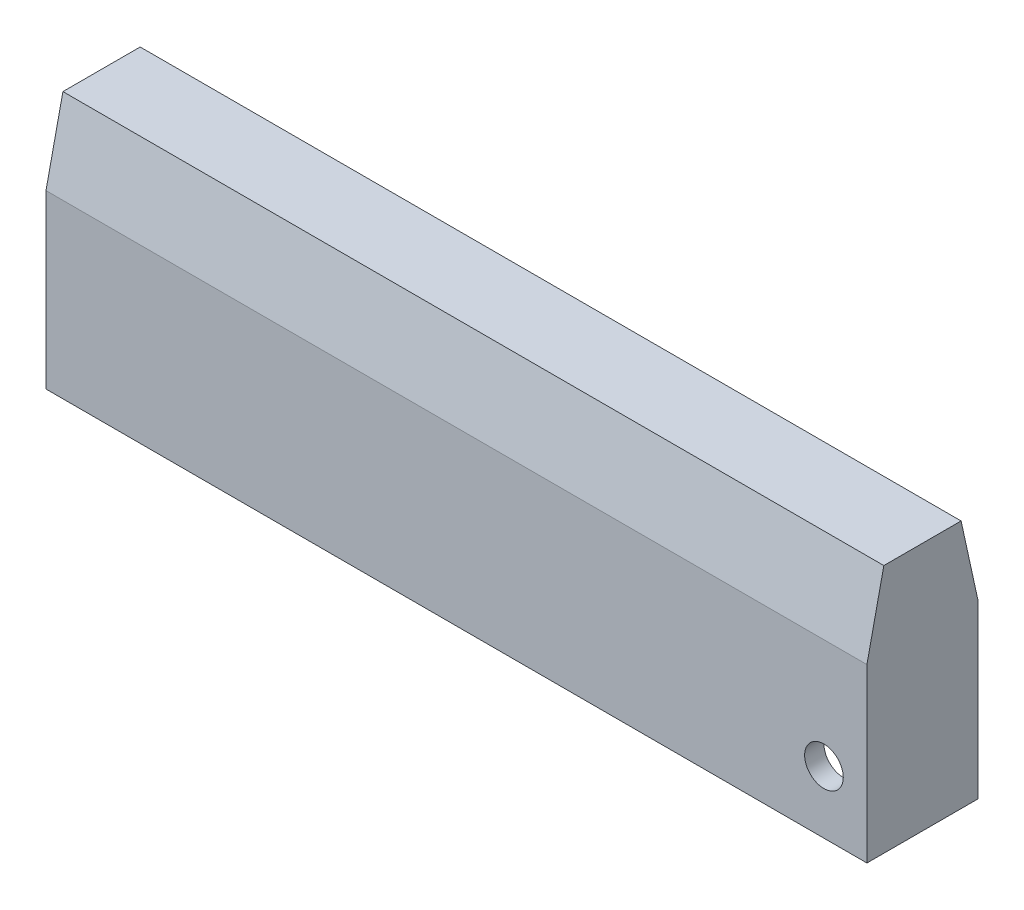
SolidWorks part; units mm, degrees
ref_plane "Front Plane" through (0, 0, 0) normal (0, 0, 1) x (1, 0, 0)
ref_plane "Top Plane" through (0, 0, 0) normal (0, 1, 0) x (1, 0, 0)
ref_plane "Right Plane" through (0, 0, 0) normal (1, 0, 0) x (0, 0, -1)
sketch "Sketch1" plane through (0, 0, 0) normal (0, 1, 0) x (1, 0, 0)
  line L1 (-69, -5.75) -> (69, -5.75)
  line L2 (-69, -5.75) -> (-69, 5.75)
  line L3 (-69, 5.75) -> (69, 5.75)
  line L4 (69, -5.75) -> (69, 5.75)
  line L5 (-69, -5.75) -> (69, 5.75) construction
  line L6 (-69, 5.75) -> (69, -5.75) construction
  point P0 (0, 0)
  dimension "D1" = 11.5
  dimension "D2" = 138
extrude "Boss-Extrude1" add sketch "Sketch1" against normal blind 17.8 and the other way blind 8 contours L2 L3 L4 L1
sketch "Sketch8" plane through (0, 0, 5.75) normal (0, 0, 1) x (1, 0, 0)
  line L0 (69, 8) -> (51.2, -17.8) construction
  line L1 (-69, -17.8) -> (69, -17.8) construction
  line L3 (60.1, -4.9) -> (69, -4.9) construction
  line L4 (69, -17.8) -> (69, 8) construction
  line L5 (64.55, -4.9) -> (64.55, -17.8) construction
  circle A0 centre (64.55, -11.35) radius 2
  dimension "D1" = 4
extrude "Cut-Extrude4" cut sketch "Sketch8" against normal up to surface (11.5 mm away) up to face at (0, -4.9, -5.75)
chamfer "Chamfer2" distance 8 distance2 1.75 1 edges at (0, 8, 5.75)
chamfer "Chamfer3" distance 1.75 distance2 8 1 edges at (0, 8, -5.75)
sketch "Sketch11" plane through (0, -17.8, 0) normal (0, -1, 0) x (1, 0, 0)
  line L0 (-69, 5.75) -> (-69, -5.75)
  line L1 (-69, 5.75) -> (-16, 5.75)
  line L2 (-69, -5.75) -> (-16, -5.75)
  line L3 (-16, 5.75) -> (-16, -5.75)
  line L4 (69, 5.75) -> (69, -5.75) construction
  dimension "D1" = 85
extrude "Cut-Extrude5" cut sketch "Sketch11" against normal up to surface (25.8 mm away) up to face at (0, 8, 0)
sketch "Sketch12" plane through (0, -17.8, 0) normal (0, -1, 0) x (1, 0, 0)
  line L0 (-16, -5.75) -> (69, 5.75) construction
  line L1 (-16, 5.75) -> (69, -5.75) construction
  line L2 (69, 5.75) -> (69, -5.75) construction
  line L3 (-14, -3.75) -> (67, -3.75)
  line L4 (-14, -3.75) -> (-14, 3.75)
  line L5 (-14, 3.75) -> (67, 3.75)
  line L6 (67, -3.75) -> (67, 3.75)
  line L7 (-14, -3.75) -> (67, 3.75) construction
  line L8 (-14, 3.75) -> (67, -3.75) construction
  line L9 (-16, 5.75) -> (69, 5.75) construction
  point P8 (26.5, 0)
  dimension "D1" = 2
  dimension "D2" = 2
extrude "Cut-Extrude6" cut sketch "Sketch12" against normal offset from surface (17.8 mm away) 8 up to face at (26.5, 8, 0)
sketch "Sketch13" plane through (0, 0, -3.75) normal (0, 0, 1) x (1, 0, 0)
  line L1 (26.5, -17.8) -> (26.5, 1.1234) construction
  line L2 (-14, -17.8) -> (67, -17.8) construction
  line L3 (-14, -14.3) -> (-14, -12.3)
  line L4 (-14, -14.3) -> (26.5, -14.3)
  line L5 (-14, -12.3) -> (26.5, -12.3)
  line L6 (26.5, -14.3) -> (26.5, -12.3)
  line L7 (-14, 0) -> (-14, -17.8) construction
  dimension "D1" = 3.5
  dimension "D2" = 2
extrude "Boss-Extrude3" add sketch "Sketch13" along normal up to surface (7.5 mm away) up to face at (26.5, -8.9, 3.75)
